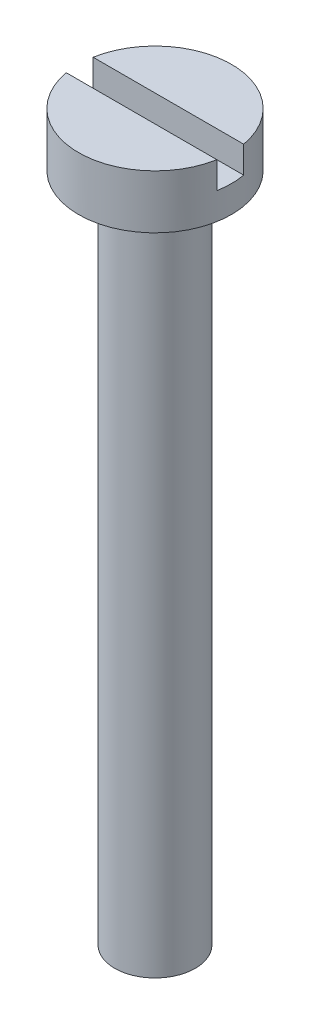
SolidWorks part; units mm, degrees
ref_plane "Front Plane" through (0, 0, 0) normal (0, 0, 1) x (1, 0, 0)
ref_plane "Top Plane" through (0, 0, 0) normal (0, 1, 0) x (1, 0, 0)
ref_plane "Right Plane" through (0, 0, 0) normal (1, 0, 0) x (0, 0, -1)
sketch "Sketch1" plane through (0, 0, 0) normal (0, 1, 0) x (1, 0, 0)
  circle A0 centre (0, 0) radius 2.85
  dimension "D1" = 5.7
extrude "Boss-Extrude1" add sketch "Sketch1" along normal blind 2
sketch "Sketch2" plane through (0, 0, 0) normal (0, 1, 0) x (1, 0, 0)
  circle A0 centre (0, 0) radius 1.5
  dimension "D1" = 3
extrude "Boss-Extrude2" add sketch "Sketch2" against normal blind 25
sketch "Sketch3" plane through (0, 2, 0) normal (0, 1, 0) x (1, 0, 0)
  line L1 (-3, -0.5) -> (3, -0.5)
  line L2 (-3, -0.5) -> (-3, 0.5)
  line L3 (-3, 0.5) -> (3, 0.5)
  line L4 (3, -0.5) -> (3, 0.5)
  line L5 (-3, -0.5) -> (3, 0.5) construction
  line L6 (-3, 0.5) -> (3, -0.5) construction
  point P0 (0, 0)
  dimension "D1" = 1
  dimension "D2" = 6
extrude "Cut-Extrude1" cut sketch "Sketch3" against normal blind 1
